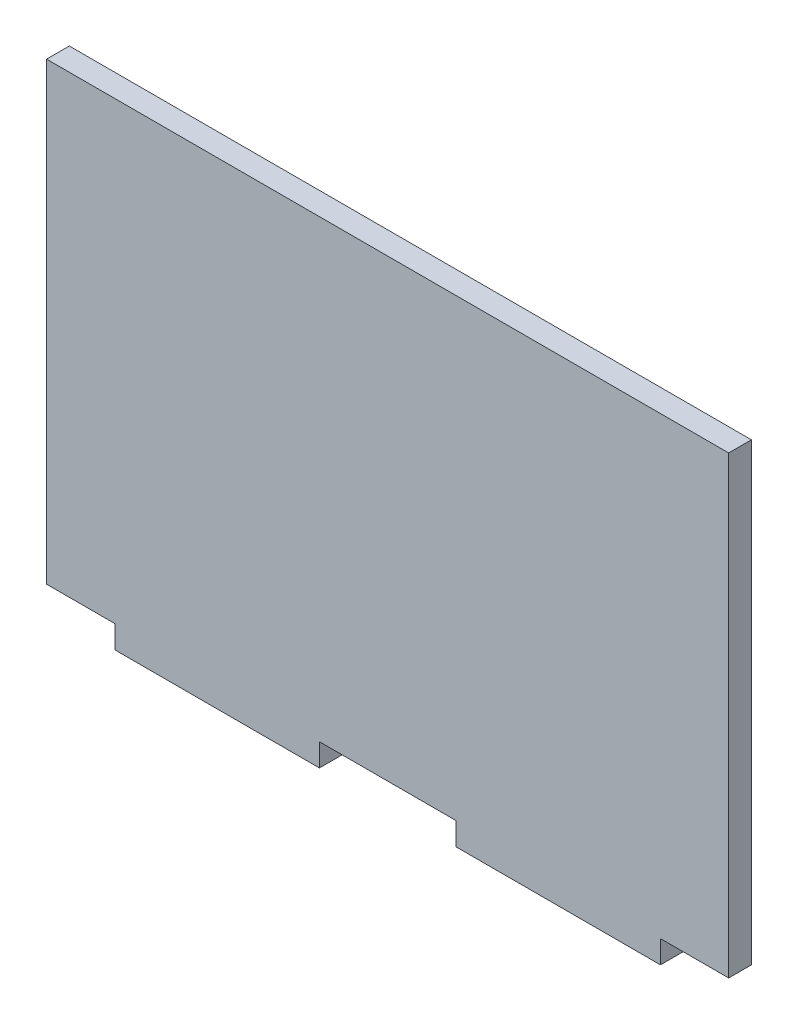
SolidWorks part; units mm, degrees
ref_plane "Alzado" through (0, 0, 0) normal (0, 0, 1) x (1, 0, 0)
ref_plane "Planta" through (0, 0, 0) normal (0, 1, 0) x (1, 0, 0)
ref_plane "Vista lateral" through (0, 0, 0) normal (1, 0, 0) x (0, 0, -1)
sketch "Croquis1" plane through (0, 0, 0) normal (0, 0, 1) x (1, 0, 0)
  line L0 (0, 50) -> (-96.0927, 50) construction
  line L1 (0, 0) -> (15, 0)
  line L2 (0, 0) -> (0, 12.5)
  line L3 (0, 100) -> (150, 100)
  line L4 (150, 0) -> (150, 100)
  line L13 (75, 0) -> (75, -39.9022) construction
  line L14 (135, -5) -> (90, -5)
  line L16 (15, 0) -> (15, -5)
  line L17 (15, -5) -> (60, -5)
  line L18 (60, 0) -> (60, -5)
  line L19 (90, 0) -> (90, -5)
  line L21 (135, 0) -> (135, -5)
  line L22 (0, 87.5) -> (0, 100)
  line L23 (0, 37.5) -> (0, 62.5)
  line L24 (60, 0) -> (90, 0)
  line L25 (135, 0) -> (150, 0)
  line L26 (0, 87.5) -> (0, 62.5)
  line L27 (0, 37.5) -> (0, 12.5)
  dimension "D1" = 150
  dimension "D2" = 100
  dimension "D6" = 45
  dimension "D7" = 15
  dimension "D8" = 5
  dimension "D9" = 15
extrude "Saliente-Extruir1" add sketch "Croquis1" along normal blind 5
